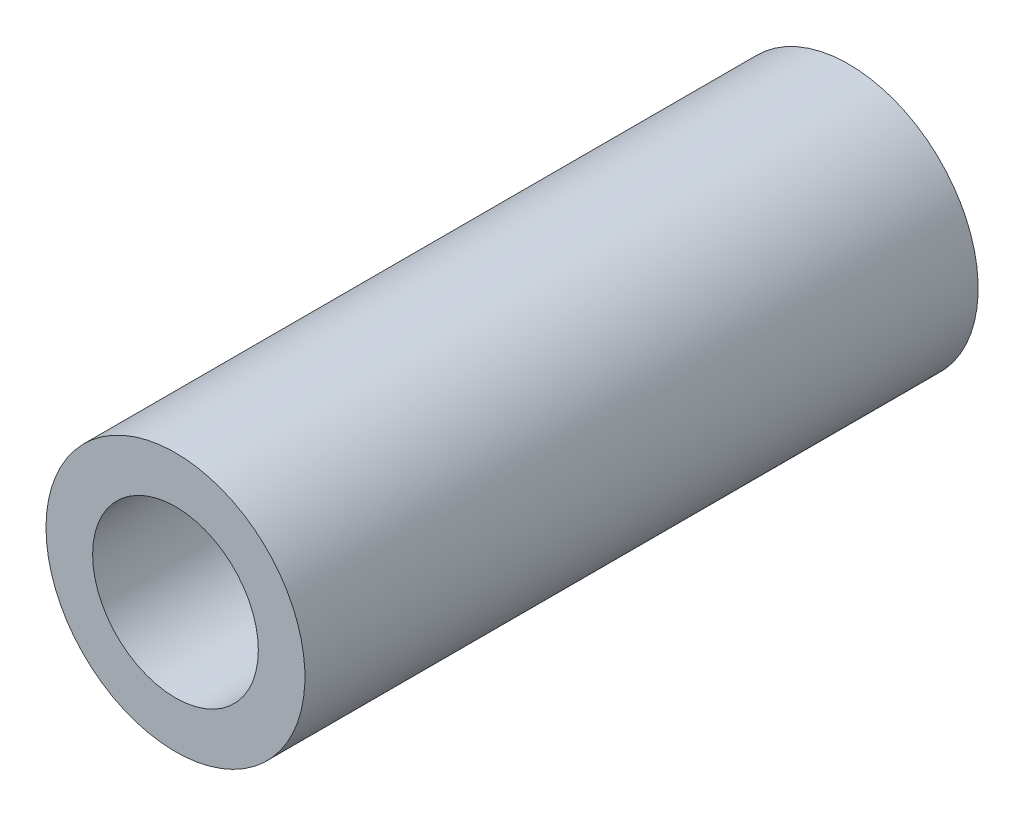
SolidWorks part; units mm, degrees
material "Nylon 6/10"
ref_plane "Front Plane" through (0, 0, 0) normal (0, 0, 1) x (1, 0, 0)
ref_plane "Top Plane" through (0, 0, 0) normal (0, 1, 0) x (1, 0, 0)
ref_plane "Right Plane" through (0, 0, 0) normal (1, 0, 0) x (0, 0, -1)
sketch "Sketch1" plane through (0, 0, 0) normal (0, 0, 1) x (1, 0, 0)
  circle A0 centre (0, 0) radius 1.6
  circle A1 centre (0, 0) radius 2.5
  dimension "D1" = 5
  dimension "D2" = 3.2
extrude "Boss-Extrude1" add sketch "Sketch1" along normal blind 13
